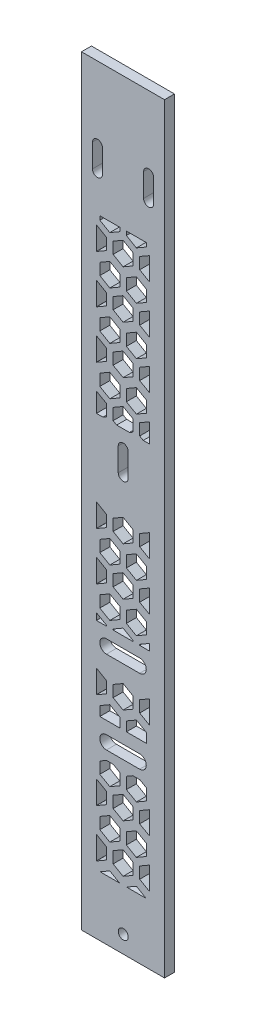
SolidWorks part; units mm, degrees
ref_plane "Front Plane" through (0, 0, 0) normal (0, 0, 1) x (1, 0, 0)
ref_plane "Top Plane" through (0, 0, 0) normal (0, 1, 0) x (1, 0, 0)
ref_plane "Right Plane" through (0, 0, 0) normal (1, 0, 0) x (0, 0, -1)
sketch "Sketch1" plane through (0, 0, 0) normal (0, 0, 1) x (1, 0, 0)
  line B0 (0, 114.5304) -> (25, 114.5304)
  line B1 (0, 114.5304) -> (0, -114.5304)
  line B2 (0, -114.5304) -> (25, -114.5304)
  line B3 (25, 114.5304) -> (25, -114.5304)
  line B4 (3.3, 89.1304) -> (0, 89.1304) construction
  line B5 (21.7, 89.1304) -> (25, 89.1304) construction
  line B6 (0, -100.1081) -> (25, -100.1081) construction
  circle B7 centre (4.8, 89.1304) radius 1.5
  circle B8 centre (20.2, 89.1304) radius 1.5
  circle B9 centre (12.5588, 13.7722) radius 1.5
  spline B10 degree 3 poles (11.075, -109.3281) (11.075, -112.3281) (14.075, -112.3281) (14.075, -109.3281) (14.075, -106.3281) (11.075, -106.3281) (11.075, -109.3281) (11.075, -112.3281) (14.075, -112.3281) knots -0.5 0 0 0 0.5 0.5 0.5 1 1 1 1.5 1.5 1.5 weights 1 0.333333 0.333333 1 0.333333 0.333333 1 0.333333 0.333333 only from (11.075, -109.3281) to (11.075, -109.3281)
sketch_block_instance "Block-sideExtraSupport-1"
sketch_block "Block-sideExtraSupport" parameters "D1"=25
extrude "Boss-Extrude1" add sketch "Sketch1" along normal blind 3 contours B1 B6 B3 B0 B9 B8 B7
sketch "Sketch2" plane through (0, 0, 3) normal (0, 0, 1) x (1, 0, 0)
  line L1 (0, -114.5304) -> (25, -114.5304) construction
  point P3 (12.5, -114.5304)
  line B0 (0, -24.3132) -> (40.525, -24.3132) construction
  line B1 (0, -24.3132) -> (0, -74.3132) construction
  line B2 (0, -74.3132) -> (40.525, -74.3132) construction
  line B3 (40.525, -24.3132) -> (40.525, -74.3132) construction
  line B4 (32.525, -24.3132) -> (28.125, -24.3132) construction
  line B5 (20.2625, -24.3132) -> (20.2625, -49.3132) construction
  line B6 (20.2625, -49.3132) -> (0, -49.3132) construction
  line B7 (20.2625, -36.8132) -> (0, -36.8132) construction
  line B8 (28.125, -64.3132) -> (32.525, -64.3132) construction
  line B9 (32.525, -64.3132) -> (32.525, -34.3132) construction
  line B10 (28.125, -64.3132) -> (28.125, -34.3132) construction
  line B11 (28.125, -34.3132) -> (32.525, -34.3132) construction
  line B12 (27.625, -64.8132) -> (33.025, -64.8132) construction
  line B13 (33.025, -64.8132) -> (33.025, -33.8132) construction
  line B14 (27.625, -33.8132) -> (33.025, -33.8132) construction
  line B15 (27.625, -64.8132) -> (27.625, -33.8132) construction
  line B16 (0, -100.1081) -> (25, -100.1081) construction
  line B17 (25, -114.5304) -> (0, -114.5304) construction
  line B18 (12.5, -100.1081) -> (12.5, -61.8132) construction
  line B19 (12.5, -114.5304) -> (12.5, -100.1081) construction
  line B20 (7.5, -36.8132) -> (17.5, -36.8132)
  line B21 (7.5, -34.8132) -> (17.5, -34.8132)
  line B22 (7.5, -38.8132) -> (17.5, -38.8132)
  line B23 (7.5, -61.8132) -> (17.5, -61.8132)
  line B24 (7.5, -63.8132) -> (17.5, -63.8132)
  line B25 (7.5, -59.8132) -> (17.5, -59.8132)
  arc B26 (7.5, -34.8132) -> (7.5, -38.8132) centre (7.5, -36.8132) ccw
  arc B27 (17.5, -38.8132) -> (17.5, -34.8132) centre (17.5, -36.8132) ccw
  arc B28 (7.5, -63.8132) -> (7.5, -59.8132) centre (7.5, -61.8132) cw
  arc B29 (17.5, -59.8132) -> (17.5, -63.8132) centre (17.5, -61.8132) cw
sketch_block_instance "Block-SidePanelSketch2-1"
sketch_block "Block-SidePanelSketch2" parameters "D1"=50, "D2"=4, "D3"=10, "D4"=8
extrude "Cut-Extrude1" cut sketch "Sketch2" against normal through all
sketch "Sketch3" plane through (0, 0, 3) normal (0, 0, 1) x (1, 0, 0)
  line L0 (12.5, 114.5304) -> (12.5, -114.5304) construction
  line L1 (0, 114.5304) -> (25, 114.5304) construction
  line L2 (0, -114.5304) -> (25, -114.5304) construction
  line L3 (4.8, 92.6304) -> (4.8, 85.6304) construction
  line L4 (6.3, 92.6304) -> (6.3, 85.6304)
  line L5 (3.3, 92.6304) -> (3.3, 85.6304)
  line L6 (20.2, 92.6304) -> (20.2, 85.6304) construction
  line L7 (18.7, 92.6304) -> (18.7, 85.6304)
  line L8 (21.7, 92.6304) -> (21.7, 85.6304)
  line L9 (12.5588, 17.2722) -> (12.5588, 10.2722) construction
  line L10 (14.0588, 17.2722) -> (14.0588, 10.2722)
  line L11 (11.0588, 17.2722) -> (11.0588, 10.2722)
  arc A1 (6.3, 92.6304) -> (3.3, 92.6304) centre (4.8, 92.6304) ccw
  arc A2 (3.3, 85.6304) -> (6.3, 85.6304) centre (4.8, 85.6304) ccw
  circle A3 centre (4.8, 89.1304) radius 1.5 construction
  arc A4 (18.7, 92.6304) -> (21.7, 92.6304) centre (20.2, 92.6304) cw
  arc A5 (21.7, 85.6304) -> (18.7, 85.6304) centre (20.2, 85.6304) cw
  arc A6 (14.0588, 17.2722) -> (11.0588, 17.2722) centre (12.5588, 17.2722) ccw
  arc A7 (11.0588, 10.2722) -> (14.0588, 10.2722) centre (12.5588, 10.2722) ccw
  circle A8 centre (12.5588, 13.7722) radius 1.5 construction
  point P6 (4.8, 89.1304)
  point P10 (12.5588, 18.7722)
  point P14 (12.5588, 13.7722)
  point P19 (4.8, 94.1304)
  point P22 (20.2, 89.1304)
  dimension "D1" = 5
  dimension "D2" = 5
extrude "Cut-Extrude2" cut sketch "Sketch3" against normal through all
sketch "Sketch4" plane through (0, 0, 3) normal (0, 0, 1) x (1, 0, 0)
  line L0 (25, 114.5304) -> (25, -114.5304) construction
  line L1 (4.5, -66.5304) -> (20.5, -66.5304)
  line L2 (4.5, -66.5304) -> (4.5, -96.5304)
  line L3 (4.5, -96.5304) -> (20.5, -96.5304)
  line L4 (20.5, -66.5304) -> (20.5, -96.5304)
  line L5 (4.5, -66.5304) -> (20.5, -96.5304) construction
  line L6 (4.5, -96.5304) -> (20.5, -66.5304) construction
  line L7 (4.5, -43.0716) -> (20.5, -43.0716)
  line L8 (4.5, -43.0716) -> (4.5, -56.0716)
  line L9 (4.5, -56.0716) -> (20.5, -56.0716)
  line L10 (20.5, -43.0716) -> (20.5, -56.0716)
  line L11 (4.5, -43.0716) -> (20.5, -56.0716) construction
  line L12 (4.5, -56.0716) -> (20.5, -43.0716) construction
  line L13 (4.5, 22.4696) -> (20.5, 22.4696)
  line L14 (4.5, 22.4696) -> (4.5, 74.5304)
  line L15 (4.5, 74.5304) -> (20.5, 74.5304)
  line L16 (20.5, 22.4696) -> (20.5, 74.5304)
  line L17 (4.5, 22.4696) -> (20.5, 74.5304) construction
  line L18 (4.5, 74.5304) -> (20.5, 22.4696) construction
  line L19 (4.5, -31.5304) -> (20.5, -31.5304)
  line L20 (4.5, -31.5304) -> (4.5, 5.4696)
  line L21 (4.5, 5.4696) -> (20.5, 5.4696)
  line L22 (20.5, -31.5304) -> (20.5, 5.4696)
  line L23 (4.5, -31.5304) -> (20.5, 5.4696) construction
  line L24 (4.5, 5.4696) -> (20.5, -31.5304) construction
  line L25 (0, 114.5304) -> (0, -114.5304) construction
  line L26 (0, -114.5304) -> (25, -114.5304) construction
  line L27 (0, 114.5304) -> (25, 114.5304) construction
  line L28 (11.5204, -100.036) -> (11.5204, -96.5719)
  line L29 (3.5204, -100.036) -> (3.5204, -96.5719)
  line L30 (3.5204, -96.5719) -> (0.5204, -94.8398)
  line L31 (0.5204, -94.8398) -> (-2.4796, -96.5719)
  line L32 (-2.4796, -96.5719) -> (-2.4796, -100.036)
  line L33 (-2.4796, -100.036) -> (0.5204, -101.7681)
  line L34 (0.5204, -101.7681) -> (3.5204, -100.036)
  line L35 (7.5204, -106.9642) -> (7.5204, -103.5001)
  line L36 (7.5204, -103.5001) -> (4.5204, -101.7681)
  line L37 (4.5204, -101.7681) -> (1.5204, -103.5001)
  line L38 (1.5204, -103.5001) -> (1.5204, -106.9642)
  line L39 (1.5204, -106.9642) -> (4.5204, -108.6963)
  line L40 (4.5204, -108.6963) -> (7.5204, -106.9642)
  line L41 (11.5204, -96.5719) -> (8.5204, -94.8398)
  line L42 (8.5204, -94.8398) -> (5.5204, -96.5719)
  line L43 (5.5204, -96.5719) -> (5.5204, -100.036)
  line L44 (5.5204, -100.036) -> (8.5204, -101.7681)
  line L45 (8.5204, -101.7681) -> (11.5204, -100.036)
  line L46 (15.5204, -106.9642) -> (15.5204, -103.5001)
  line L47 (15.5204, -103.5001) -> (12.5204, -101.7681)
  line L48 (12.5204, -101.7681) -> (9.5204, -103.5001)
  line L49 (9.5204, -103.5001) -> (9.5204, -106.9642)
  line L50 (9.5204, -106.9642) -> (12.5204, -108.6963)
  line L51 (12.5204, -108.6963) -> (15.5204, -106.9642)
  line L52 (19.5204, -100.036) -> (19.5204, -96.5719)
  line L53 (19.5204, -96.5719) -> (16.5204, -94.8398)
  line L54 (16.5204, -94.8398) -> (13.5204, -96.5719)
  line L55 (13.5204, -96.5719) -> (13.5204, -100.036)
  line L56 (13.5204, -100.036) -> (16.5204, -101.7681)
  line L57 (16.5204, -101.7681) -> (19.5204, -100.036)
  line L58 (23.5204, -106.9642) -> (23.5204, -103.5001)
  line L59 (23.5204, -103.5001) -> (20.5204, -101.7681)
  line L60 (20.5204, -101.7681) -> (17.5204, -103.5001)
  line L61 (17.5204, -103.5001) -> (17.5204, -106.9642)
  line L62 (17.5204, -106.9642) -> (20.5204, -108.6963)
  line L63 (20.5204, -108.6963) -> (23.5204, -106.9642)
  line L64 (11.5204, -85.586) -> (11.5204, -82.1219)
  line L65 (11.5204, -82.1219) -> (8.5204, -80.3898)
  line L66 (8.5204, -80.3898) -> (5.5204, -82.1219)
  line L67 (5.5204, -82.1219) -> (5.5204, -85.586)
  line L68 (5.5204, -85.586) -> (8.5204, -87.3181)
  line L69 (8.5204, -87.3181) -> (11.5204, -85.586)
  line L70 (15.5204, -92.5142) -> (15.5204, -89.0501)
  line L71 (15.5204, -89.0501) -> (12.5204, -87.3181)
  line L72 (12.5204, -87.3181) -> (9.5204, -89.0501)
  line L73 (9.5204, -89.0501) -> (9.5204, -92.5142)
  line L74 (9.5204, -92.5142) -> (12.5204, -94.2463)
  line L75 (12.5204, -94.2463) -> (15.5204, -92.5142)
  line L76 (19.5204, -85.586) -> (19.5204, -82.1219)
  line L77 (19.5204, -82.1219) -> (16.5204, -80.3898)
  line L78 (16.5204, -80.3898) -> (13.5204, -82.1219)
  line L79 (13.5204, -82.1219) -> (13.5204, -85.586)
  line L80 (13.5204, -85.586) -> (16.5204, -87.3181)
  line L81 (16.5204, -87.3181) -> (19.5204, -85.586)
  line L82 (23.5204, -92.5142) -> (23.5204, -89.0501)
  line L83 (23.5204, -89.0501) -> (20.5204, -87.3181)
  line L84 (20.5204, -87.3181) -> (17.5204, -89.0501)
  line L85 (17.5204, -89.0501) -> (17.5204, -92.5142)
  line L86 (17.5204, -92.5142) -> (20.5204, -94.2463)
  line L87 (20.5204, -94.2463) -> (23.5204, -92.5142)
  line L88 (11.5204, -71.136) -> (11.5204, -67.6719)
  line L89 (11.5204, -67.6719) -> (8.5204, -65.9398)
  line L90 (8.5204, -65.9398) -> (5.5204, -67.6719)
  line L91 (5.5204, -67.6719) -> (5.5204, -71.136)
  line L92 (5.5204, -71.136) -> (8.5204, -72.8681)
  line L93 (8.5204, -72.8681) -> (11.5204, -71.136)
  line L94 (15.5204, -78.0642) -> (15.5204, -74.6001)
  line L95 (15.5204, -74.6001) -> (12.5204, -72.8681)
  line L96 (12.5204, -72.8681) -> (9.5204, -74.6001)
  line L97 (9.5204, -74.6001) -> (9.5204, -78.0642)
  line L98 (9.5204, -78.0642) -> (12.5204, -79.7963)
  line L99 (12.5204, -79.7963) -> (15.5204, -78.0642)
  line L100 (19.5204, -71.136) -> (19.5204, -67.6719)
  line L101 (19.5204, -67.6719) -> (16.5204, -65.9398)
  line L102 (16.5204, -65.9398) -> (13.5204, -67.6719)
  line L103 (13.5204, -67.6719) -> (13.5204, -71.136)
  line L104 (13.5204, -71.136) -> (16.5204, -72.8681)
  line L105 (16.5204, -72.8681) -> (19.5204, -71.136)
  line L106 (23.5204, -78.0642) -> (23.5204, -74.6001)
  line L107 (23.5204, -74.6001) -> (20.5204, -72.8681)
  line L108 (20.5204, -72.8681) -> (17.5204, -74.6001)
  line L109 (17.5204, -74.6001) -> (17.5204, -78.0642)
  line L110 (17.5204, -78.0642) -> (20.5204, -79.7963)
  line L111 (20.5204, -79.7963) -> (23.5204, -78.0642)
  line L112 (11.5204, -56.686) -> (11.5204, -53.2219)
  line L113 (11.5204, -53.2219) -> (8.5204, -51.4898)
  line L114 (8.5204, -51.4898) -> (5.5204, -53.2219)
  line L115 (5.5204, -53.2219) -> (5.5204, -56.686)
  line L116 (5.5204, -56.686) -> (8.5204, -58.4181)
  line L117 (8.5204, -58.4181) -> (11.5204, -56.686)
  line L118 (15.5204, -63.6142) -> (15.5204, -60.1501)
  line L119 (15.5204, -60.1501) -> (12.5204, -58.4181)
  line L120 (12.5204, -58.4181) -> (9.5204, -60.1501)
  line L121 (9.5204, -60.1501) -> (9.5204, -63.6142)
  line L122 (9.5204, -63.6142) -> (12.5204, -65.3463)
  line L123 (12.5204, -65.3463) -> (15.5204, -63.6142)
  line L124 (19.5204, -56.686) -> (19.5204, -53.2219)
  line L125 (19.5204, -53.2219) -> (16.5204, -51.4898)
  line L126 (16.5204, -51.4898) -> (13.5204, -53.2219)
  line L127 (13.5204, -53.2219) -> (13.5204, -56.686)
  line L128 (13.5204, -56.686) -> (16.5204, -58.4181)
  line L129 (16.5204, -58.4181) -> (19.5204, -56.686)
  line L130 (23.5204, -63.6142) -> (23.5204, -60.1501)
  line L131 (23.5204, -60.1501) -> (20.5204, -58.4181)
  line L132 (20.5204, -58.4181) -> (17.5204, -60.1501)
  line L133 (17.5204, -60.1501) -> (17.5204, -63.6142)
  line L134 (17.5204, -63.6142) -> (20.5204, -65.3463)
  line L135 (20.5204, -65.3463) -> (23.5204, -63.6142)
  line L136 (11.5204, -42.236) -> (11.5204, -38.7719)
  line L137 (11.5204, -38.7719) -> (8.5204, -37.0398)
  line L138 (8.5204, -37.0398) -> (5.5204, -38.7719)
  line L139 (5.5204, -38.7719) -> (5.5204, -42.236)
  line L140 (5.5204, -42.236) -> (8.5204, -43.9681)
  line L141 (8.5204, -43.9681) -> (11.5204, -42.236)
  line L142 (15.5204, -49.1642) -> (15.5204, -45.7001)
  line L143 (15.5204, -45.7001) -> (12.5204, -43.9681)
  line L144 (12.5204, -43.9681) -> (9.5204, -45.7001)
  line L145 (9.5204, -45.7001) -> (9.5204, -49.1642)
  line L146 (9.5204, -49.1642) -> (12.5204, -50.8963)
  line L147 (12.5204, -50.8963) -> (15.5204, -49.1642)
  line L148 (19.5204, -42.236) -> (19.5204, -38.7719)
  line L149 (19.5204, -38.7719) -> (16.5204, -37.0398)
  line L150 (16.5204, -37.0398) -> (13.5204, -38.7719)
  line L151 (13.5204, -38.7719) -> (13.5204, -42.236)
  line L152 (13.5204, -42.236) -> (16.5204, -43.9681)
  line L153 (16.5204, -43.9681) -> (19.5204, -42.236)
  line L154 (23.5204, -49.1642) -> (23.5204, -45.7001)
  line L155 (23.5204, -45.7001) -> (20.5204, -43.9681)
  line L156 (20.5204, -43.9681) -> (17.5204, -45.7001)
  line L157 (17.5204, -45.7001) -> (17.5204, -49.1642)
  line L158 (17.5204, -49.1642) -> (20.5204, -50.8963)
  line L159 (20.5204, -50.8963) -> (23.5204, -49.1642)
  line L160 (11.5204, -27.786) -> (11.5204, -24.3219)
  line L161 (11.5204, -24.3219) -> (8.5204, -22.5898)
  line L162 (8.5204, -22.5898) -> (5.5204, -24.3219)
  line L163 (5.5204, -24.3219) -> (5.5204, -27.786)
  line L164 (5.5204, -27.786) -> (8.5204, -29.5181)
  line L165 (8.5204, -29.5181) -> (11.5204, -27.786)
  line L166 (15.5204, -34.7142) -> (15.5204, -31.2501)
  line L167 (15.5204, -31.2501) -> (12.5204, -29.5181)
  line L168 (12.5204, -29.5181) -> (9.5204, -31.2501)
  line L169 (9.5204, -31.2501) -> (9.5204, -34.7142)
  line L170 (9.5204, -34.7142) -> (12.5204, -36.4463)
  line L171 (12.5204, -36.4463) -> (15.5204, -34.7142)
  line L172 (19.5204, -27.786) -> (19.5204, -24.3219)
  line L173 (19.5204, -24.3219) -> (16.5204, -22.5898)
  line L174 (16.5204, -22.5898) -> (13.5204, -24.3219)
  line L175 (13.5204, -24.3219) -> (13.5204, -27.786)
  line L176 (13.5204, -27.786) -> (16.5204, -29.5181)
  line L177 (16.5204, -29.5181) -> (19.5204, -27.786)
  line L178 (23.5204, -34.7142) -> (23.5204, -31.2501)
  line L179 (23.5204, -31.2501) -> (20.5204, -29.5181)
  line L180 (20.5204, -29.5181) -> (17.5204, -31.2501)
  line L181 (17.5204, -31.2501) -> (17.5204, -34.7142)
  line L182 (17.5204, -34.7142) -> (20.5204, -36.4463)
  line L183 (20.5204, -36.4463) -> (23.5204, -34.7142)
  line L184 (11.5204, -13.336) -> (11.5204, -9.8719)
  line L185 (11.5204, -9.8719) -> (8.5204, -8.1398)
  line L186 (8.5204, -8.1398) -> (5.5204, -9.8719)
  line L187 (5.5204, -9.8719) -> (5.5204, -13.336)
  line L188 (5.5204, -13.336) -> (8.5204, -15.0681)
  line L189 (8.5204, -15.0681) -> (11.5204, -13.336)
  line L190 (15.5204, -20.2642) -> (15.5204, -16.8001)
  line L191 (15.5204, -16.8001) -> (12.5204, -15.0681)
  line L192 (12.5204, -15.0681) -> (9.5204, -16.8001)
  line L193 (9.5204, -16.8001) -> (9.5204, -20.2642)
  line L194 (9.5204, -20.2642) -> (12.5204, -21.9963)
  line L195 (12.5204, -21.9963) -> (15.5204, -20.2642)
  line L196 (19.5204, -13.336) -> (19.5204, -9.8719)
  line L197 (19.5204, -9.8719) -> (16.5204, -8.1398)
  line L198 (16.5204, -8.1398) -> (13.5204, -9.8719)
  line L199 (13.5204, -9.8719) -> (13.5204, -13.336)
  line L200 (13.5204, -13.336) -> (16.5204, -15.0681)
  line L201 (16.5204, -15.0681) -> (19.5204, -13.336)
  line L202 (23.5204, -20.2642) -> (23.5204, -16.8001)
  line L203 (23.5204, -16.8001) -> (20.5204, -15.0681)
  line L204 (20.5204, -15.0681) -> (17.5204, -16.8001)
  line L205 (17.5204, -16.8001) -> (17.5204, -20.2642)
  line L206 (17.5204, -20.2642) -> (20.5204, -21.9963)
  line L207 (20.5204, -21.9963) -> (23.5204, -20.2642)
  line L208 (11.5204, 1.114) -> (11.5204, 4.5781)
  line L209 (11.5204, 4.5781) -> (8.5204, 6.3102)
  line L210 (8.5204, 6.3102) -> (5.5204, 4.5781)
  line L211 (5.5204, 4.5781) -> (5.5204, 1.114)
  line L212 (5.5204, 1.114) -> (8.5204, -0.6181)
  line L213 (8.5204, -0.6181) -> (11.5204, 1.114)
  line L214 (15.5204, -5.8142) -> (15.5204, -2.3501)
  line L215 (15.5204, -2.3501) -> (12.5204, -0.6181)
  line L216 (12.5204, -0.6181) -> (9.5204, -2.3501)
  line L217 (9.5204, -2.3501) -> (9.5204, -5.8142)
  line L218 (9.5204, -5.8142) -> (12.5204, -7.5463)
  line L219 (12.5204, -7.5463) -> (15.5204, -5.8142)
  line L220 (19.5204, 1.114) -> (19.5204, 4.5781)
  line L221 (19.5204, 4.5781) -> (16.5204, 6.3102)
  line L222 (16.5204, 6.3102) -> (13.5204, 4.5781)
  line L223 (13.5204, 4.5781) -> (13.5204, 1.114)
  line L224 (13.5204, 1.114) -> (16.5204, -0.6181)
  line L225 (16.5204, -0.6181) -> (19.5204, 1.114)
  line L226 (23.5204, -5.8142) -> (23.5204, -2.3501)
  line L227 (23.5204, -2.3501) -> (20.5204, -0.6181)
  line L228 (20.5204, -0.6181) -> (17.5204, -2.3501)
  line L229 (17.5204, -2.3501) -> (17.5204, -5.8142)
  line L230 (17.5204, -5.8142) -> (20.5204, -7.5463)
  line L231 (20.5204, -7.5463) -> (23.5204, -5.8142)
  line L232 (11.5204, 15.564) -> (11.5204, 19.0281)
  line L233 (11.5204, 19.0281) -> (8.5204, 20.7602)
  line L234 (8.5204, 20.7602) -> (5.5204, 19.0281)
  line L235 (5.5204, 19.0281) -> (5.5204, 15.564)
  line L236 (5.5204, 15.564) -> (8.5204, 13.8319)
  line L237 (8.5204, 13.8319) -> (11.5204, 15.564)
  line L238 (15.5204, 8.6358) -> (15.5204, 12.0999)
  line L239 (15.5204, 12.0999) -> (12.5204, 13.8319)
  line L240 (12.5204, 13.8319) -> (9.5204, 12.0999)
  line L241 (9.5204, 12.0999) -> (9.5204, 8.6358)
  line L242 (9.5204, 8.6358) -> (12.5204, 6.9037)
  line L243 (12.5204, 6.9037) -> (15.5204, 8.6358)
  line L244 (19.5204, 15.564) -> (19.5204, 19.0281)
  line L245 (19.5204, 19.0281) -> (16.5204, 20.7602)
  line L246 (16.5204, 20.7602) -> (13.5204, 19.0281)
  line L247 (13.5204, 19.0281) -> (13.5204, 15.564)
  line L248 (13.5204, 15.564) -> (16.5204, 13.8319)
  line L249 (16.5204, 13.8319) -> (19.5204, 15.564)
  line L250 (23.5204, 8.6358) -> (23.5204, 12.0999)
  line L251 (23.5204, 12.0999) -> (20.5204, 13.8319)
  line L252 (20.5204, 13.8319) -> (17.5204, 12.0999)
  line L253 (17.5204, 12.0999) -> (17.5204, 8.6358)
  line L254 (17.5204, 8.6358) -> (20.5204, 6.9037)
  line L255 (20.5204, 6.9037) -> (23.5204, 8.6358)
  line L256 (11.5204, 30.014) -> (11.5204, 33.4781)
  line L257 (11.5204, 33.4781) -> (8.5204, 35.2102)
  line L258 (8.5204, 35.2102) -> (5.5204, 33.4781)
  line L259 (5.5204, 33.4781) -> (5.5204, 30.014)
  line L260 (5.5204, 30.014) -> (8.5204, 28.2819)
  line L261 (8.5204, 28.2819) -> (11.5204, 30.014)
  line L262 (15.5204, 23.0858) -> (15.5204, 26.5499)
  line L263 (15.5204, 26.5499) -> (12.5204, 28.2819)
  line L264 (12.5204, 28.2819) -> (9.5204, 26.5499)
  line L265 (9.5204, 26.5499) -> (9.5204, 23.0858)
  line L266 (9.5204, 23.0858) -> (12.5204, 21.3537)
  line L267 (12.5204, 21.3537) -> (15.5204, 23.0858)
  line L268 (19.5204, 30.014) -> (19.5204, 33.4781)
  line L269 (19.5204, 33.4781) -> (16.5204, 35.2102)
  line L270 (16.5204, 35.2102) -> (13.5204, 33.4781)
  line L271 (13.5204, 33.4781) -> (13.5204, 30.014)
  line L272 (13.5204, 30.014) -> (16.5204, 28.2819)
  line L273 (16.5204, 28.2819) -> (19.5204, 30.014)
  line L274 (23.5204, 23.0858) -> (23.5204, 26.5499)
  line L275 (23.5204, 26.5499) -> (20.5204, 28.2819)
  line L276 (20.5204, 28.2819) -> (17.5204, 26.5499)
  line L277 (17.5204, 26.5499) -> (17.5204, 23.0858)
  line L278 (17.5204, 23.0858) -> (20.5204, 21.3537)
  line L279 (20.5204, 21.3537) -> (23.5204, 23.0858)
  line L280 (11.5204, 44.464) -> (11.5204, 47.9281)
  line L281 (11.5204, 47.9281) -> (8.5204, 49.6602)
  line L282 (8.5204, 49.6602) -> (5.5204, 47.9281)
  line L283 (5.5204, 47.9281) -> (5.5204, 44.464)
  line L284 (5.5204, 44.464) -> (8.5204, 42.7319)
  line L285 (8.5204, 42.7319) -> (11.5204, 44.464)
  line L286 (15.5204, 37.5358) -> (15.5204, 40.9999)
  line L287 (15.5204, 40.9999) -> (12.5204, 42.7319)
  line L288 (12.5204, 42.7319) -> (9.5204, 40.9999)
  line L289 (9.5204, 40.9999) -> (9.5204, 37.5358)
  line L290 (9.5204, 37.5358) -> (12.5204, 35.8037)
  line L291 (12.5204, 35.8037) -> (15.5204, 37.5358)
  line L292 (19.5204, 44.464) -> (19.5204, 47.9281)
  line L293 (19.5204, 47.9281) -> (16.5204, 49.6602)
  line L294 (16.5204, 49.6602) -> (13.5204, 47.9281)
  line L295 (13.5204, 47.9281) -> (13.5204, 44.464)
  line L296 (13.5204, 44.464) -> (16.5204, 42.7319)
  line L297 (16.5204, 42.7319) -> (19.5204, 44.464)
  line L298 (23.5204, 37.5358) -> (23.5204, 40.9999)
  line L299 (23.5204, 40.9999) -> (20.5204, 42.7319)
  line L300 (20.5204, 42.7319) -> (17.5204, 40.9999)
  line L301 (17.5204, 40.9999) -> (17.5204, 37.5358)
  line L302 (17.5204, 37.5358) -> (20.5204, 35.8037)
  line L303 (20.5204, 35.8037) -> (23.5204, 37.5358)
  line L304 (11.5204, 58.914) -> (11.5204, 62.3781)
  line L305 (11.5204, 62.3781) -> (8.5204, 64.1102)
  line L306 (8.5204, 64.1102) -> (5.5204, 62.3781)
  line L307 (5.5204, 62.3781) -> (5.5204, 58.914)
  line L308 (5.5204, 58.914) -> (8.5204, 57.1819)
  line L309 (8.5204, 57.1819) -> (11.5204, 58.914)
  line L310 (15.5204, 51.9858) -> (15.5204, 55.4499)
  line L311 (15.5204, 55.4499) -> (12.5204, 57.1819)
  line L312 (12.5204, 57.1819) -> (9.5204, 55.4499)
  line L313 (9.5204, 55.4499) -> (9.5204, 51.9858)
  line L314 (9.5204, 51.9858) -> (12.5204, 50.2537)
  line L315 (12.5204, 50.2537) -> (15.5204, 51.9858)
  line L316 (19.5204, 58.914) -> (19.5204, 62.3781)
  line L317 (19.5204, 62.3781) -> (16.5204, 64.1102)
  line L318 (16.5204, 64.1102) -> (13.5204, 62.3781)
  line L319 (13.5204, 62.3781) -> (13.5204, 58.914)
  line L320 (13.5204, 58.914) -> (16.5204, 57.1819)
  line L321 (16.5204, 57.1819) -> (19.5204, 58.914)
  line L322 (23.5204, 51.9858) -> (23.5204, 55.4499)
  line L323 (23.5204, 55.4499) -> (20.5204, 57.1819)
  line L324 (20.5204, 57.1819) -> (17.5204, 55.4499)
  line L325 (17.5204, 55.4499) -> (17.5204, 51.9858)
  line L326 (17.5204, 51.9858) -> (20.5204, 50.2537)
  line L327 (20.5204, 50.2537) -> (23.5204, 51.9858)
  line L328 (11.5204, 73.364) -> (11.5204, 76.8281)
  line L329 (11.5204, 76.8281) -> (8.5204, 78.5602)
  line L330 (8.5204, 78.5602) -> (5.5204, 76.8281)
  line L331 (5.5204, 76.8281) -> (5.5204, 73.364)
  line L332 (5.5204, 73.364) -> (8.5204, 71.6319)
  line L333 (8.5204, 71.6319) -> (11.5204, 73.364)
  line L334 (15.5204, 66.4358) -> (15.5204, 69.8999)
  line L335 (15.5204, 69.8999) -> (12.5204, 71.6319)
  line L336 (12.5204, 71.6319) -> (9.5204, 69.8999)
  line L337 (9.5204, 69.8999) -> (9.5204, 66.4358)
  line L338 (9.5204, 66.4358) -> (12.5204, 64.7037)
  line L339 (12.5204, 64.7037) -> (15.5204, 66.4358)
  line L340 (19.5204, 73.364) -> (19.5204, 76.8281)
  line L341 (19.5204, 76.8281) -> (16.5204, 78.5602)
  line L342 (16.5204, 78.5602) -> (13.5204, 76.8281)
  line L343 (13.5204, 76.8281) -> (13.5204, 73.364)
  line L344 (13.5204, 73.364) -> (16.5204, 71.6319)
  line L345 (16.5204, 71.6319) -> (19.5204, 73.364)
  line L346 (23.5204, 66.4358) -> (23.5204, 69.8999)
  line L347 (23.5204, 69.8999) -> (20.5204, 71.6319)
  line L348 (20.5204, 71.6319) -> (17.5204, 69.8999)
  line L349 (17.5204, 69.8999) -> (17.5204, 66.4358)
  line L350 (17.5204, 66.4358) -> (20.5204, 64.7037)
  line L351 (20.5204, 64.7037) -> (23.5204, 66.4358)
  line L352 (3.5204, -85.586) -> (3.5204, -82.1219)
  line L353 (3.5204, -82.1219) -> (0.5204, -80.3898)
  line L354 (0.5204, -80.3898) -> (-2.4796, -82.1219)
  line L355 (-2.4796, -82.1219) -> (-2.4796, -85.586)
  line L356 (-2.4796, -85.586) -> (0.5204, -87.3181)
  line L357 (0.5204, -87.3181) -> (3.5204, -85.586)
  line L358 (7.5204, -92.5142) -> (7.5204, -89.0501)
  line L359 (7.5204, -89.0501) -> (4.5204, -87.3181)
  line L360 (4.5204, -87.3181) -> (1.5204, -89.0501)
  line L361 (1.5204, -89.0501) -> (1.5204, -92.5142)
  line L362 (1.5204, -92.5142) -> (4.5204, -94.2463)
  line L363 (4.5204, -94.2463) -> (7.5204, -92.5142)
  line L364 (3.5204, -71.136) -> (3.5204, -67.6719)
  line L365 (3.5204, -67.6719) -> (0.5204, -65.9398)
  line L366 (0.5204, -65.9398) -> (-2.4796, -67.6719)
  line L367 (-2.4796, -67.6719) -> (-2.4796, -71.136)
  line L368 (-2.4796, -71.136) -> (0.5204, -72.8681)
  line L369 (0.5204, -72.8681) -> (3.5204, -71.136)
  line L370 (7.5204, -78.0642) -> (7.5204, -74.6001)
  line L371 (7.5204, -74.6001) -> (4.5204, -72.8681)
  line L372 (4.5204, -72.8681) -> (1.5204, -74.6001)
  line L373 (1.5204, -74.6001) -> (1.5204, -78.0642)
  line L374 (1.5204, -78.0642) -> (4.5204, -79.7963)
  line L375 (4.5204, -79.7963) -> (7.5204, -78.0642)
  line L376 (3.5204, -56.686) -> (3.5204, -53.2219)
  line L377 (3.5204, -53.2219) -> (0.5204, -51.4898)
  line L378 (0.5204, -51.4898) -> (-2.4796, -53.2219)
  line L379 (-2.4796, -53.2219) -> (-2.4796, -56.686)
  line L380 (-2.4796, -56.686) -> (0.5204, -58.4181)
  line L381 (0.5204, -58.4181) -> (3.5204, -56.686)
  line L382 (7.5204, -63.6142) -> (7.5204, -60.1501)
  line L383 (7.5204, -60.1501) -> (4.5204, -58.4181)
  line L384 (4.5204, -58.4181) -> (1.5204, -60.1501)
  line L385 (1.5204, -60.1501) -> (1.5204, -63.6142)
  line L386 (1.5204, -63.6142) -> (4.5204, -65.3463)
  line L387 (4.5204, -65.3463) -> (7.5204, -63.6142)
  line L388 (3.5204, -42.236) -> (3.5204, -38.7719)
  line L389 (3.5204, -38.7719) -> (0.5204, -37.0398)
  line L390 (0.5204, -37.0398) -> (-2.4796, -38.7719)
  line L391 (-2.4796, -38.7719) -> (-2.4796, -42.236)
  line L392 (-2.4796, -42.236) -> (0.5204, -43.9681)
  line L393 (0.5204, -43.9681) -> (3.5204, -42.236)
  line L394 (7.5204, -49.1642) -> (7.5204, -45.7001)
  line L395 (7.5204, -45.7001) -> (4.5204, -43.9681)
  line L396 (4.5204, -43.9681) -> (1.5204, -45.7001)
  line L397 (1.5204, -45.7001) -> (1.5204, -49.1642)
  line L398 (1.5204, -49.1642) -> (4.5204, -50.8963)
  line L399 (4.5204, -50.8963) -> (7.5204, -49.1642)
  line L400 (3.5204, -27.786) -> (3.5204, -24.3219)
  line L401 (3.5204, -24.3219) -> (0.5204, -22.5898)
  line L402 (0.5204, -22.5898) -> (-2.4796, -24.3219)
  line L403 (-2.4796, -24.3219) -> (-2.4796, -27.786)
  line L404 (-2.4796, -27.786) -> (0.5204, -29.5181)
  line L405 (0.5204, -29.5181) -> (3.5204, -27.786)
  line L406 (7.5204, -34.7142) -> (7.5204, -31.2501)
  line L407 (7.5204, -31.2501) -> (4.5204, -29.5181)
  line L408 (4.5204, -29.5181) -> (1.5204, -31.2501)
  line L409 (1.5204, -31.2501) -> (1.5204, -34.7142)
  line L410 (1.5204, -34.7142) -> (4.5204, -36.4463)
  line L411 (4.5204, -36.4463) -> (7.5204, -34.7142)
  line L412 (3.5204, -13.336) -> (3.5204, -9.8719)
  line L413 (3.5204, -9.8719) -> (0.5204, -8.1398)
  line L414 (0.5204, -8.1398) -> (-2.4796, -9.8719)
  line L415 (-2.4796, -9.8719) -> (-2.4796, -13.336)
  line L416 (-2.4796, -13.336) -> (0.5204, -15.0681)
  line L417 (0.5204, -15.0681) -> (3.5204, -13.336)
  line L418 (7.5204, -20.2642) -> (7.5204, -16.8001)
  line L419 (7.5204, -16.8001) -> (4.5204, -15.0681)
  line L420 (4.5204, -15.0681) -> (1.5204, -16.8001)
  line L421 (1.5204, -16.8001) -> (1.5204, -20.2642)
  line L422 (1.5204, -20.2642) -> (4.5204, -21.9963)
  line L423 (4.5204, -21.9963) -> (7.5204, -20.2642)
  line L424 (3.5204, 1.114) -> (3.5204, 4.5781)
  line L425 (3.5204, 4.5781) -> (0.5204, 6.3102)
  line L426 (0.5204, 6.3102) -> (-2.4796, 4.5781)
  line L427 (-2.4796, 4.5781) -> (-2.4796, 1.114)
  line L428 (-2.4796, 1.114) -> (0.5204, -0.6181)
  line L429 (0.5204, -0.6181) -> (3.5204, 1.114)
  line L430 (7.5204, -5.8142) -> (7.5204, -2.3501)
  line L431 (7.5204, -2.3501) -> (4.5204, -0.6181)
  line L432 (4.5204, -0.6181) -> (1.5204, -2.3501)
  line L433 (1.5204, -2.3501) -> (1.5204, -5.8142)
  line L434 (1.5204, -5.8142) -> (4.5204, -7.5463)
  line L435 (4.5204, -7.5463) -> (7.5204, -5.8142)
  line L436 (3.5204, 15.564) -> (3.5204, 19.0281)
  line L437 (3.5204, 19.0281) -> (0.5204, 20.7602)
  line L438 (0.5204, 20.7602) -> (-2.4796, 19.0281)
  line L439 (-2.4796, 19.0281) -> (-2.4796, 15.564)
  line L440 (-2.4796, 15.564) -> (0.5204, 13.8319)
  line L441 (0.5204, 13.8319) -> (3.5204, 15.564)
  line L442 (7.5204, 8.6358) -> (7.5204, 12.0999)
  line L443 (7.5204, 12.0999) -> (4.5204, 13.8319)
  line L444 (4.5204, 13.8319) -> (1.5204, 12.0999)
  line L445 (1.5204, 12.0999) -> (1.5204, 8.6358)
  line L446 (1.5204, 8.6358) -> (4.5204, 6.9037)
  line L447 (4.5204, 6.9037) -> (7.5204, 8.6358)
  line L448 (3.5204, 30.014) -> (3.5204, 33.4781)
  line L449 (3.5204, 33.4781) -> (0.5204, 35.2102)
  line L450 (0.5204, 35.2102) -> (-2.4796, 33.4781)
  line L451 (-2.4796, 33.4781) -> (-2.4796, 30.014)
  line L452 (-2.4796, 30.014) -> (0.5204, 28.2819)
  line L453 (0.5204, 28.2819) -> (3.5204, 30.014)
  line L454 (7.5204, 23.0858) -> (7.5204, 26.5499)
  line L455 (7.5204, 26.5499) -> (4.5204, 28.2819)
  line L456 (4.5204, 28.2819) -> (1.5204, 26.5499)
  line L457 (1.5204, 26.5499) -> (1.5204, 23.0858)
  line L458 (1.5204, 23.0858) -> (4.5204, 21.3537)
  line L459 (4.5204, 21.3537) -> (7.5204, 23.0858)
  line L460 (3.5204, 44.464) -> (3.5204, 47.9281)
  line L461 (3.5204, 47.9281) -> (0.5204, 49.6602)
  line L462 (0.5204, 49.6602) -> (-2.4796, 47.9281)
  line L463 (-2.4796, 47.9281) -> (-2.4796, 44.464)
  line L464 (-2.4796, 44.464) -> (0.5204, 42.7319)
  line L465 (0.5204, 42.7319) -> (3.5204, 44.464)
  line L466 (7.5204, 37.5358) -> (7.5204, 40.9999)
  line L467 (7.5204, 40.9999) -> (4.5204, 42.7319)
  line L468 (4.5204, 42.7319) -> (1.5204, 40.9999)
  line L469 (1.5204, 40.9999) -> (1.5204, 37.5358)
  line L470 (1.5204, 37.5358) -> (4.5204, 35.8037)
  line L471 (4.5204, 35.8037) -> (7.5204, 37.5358)
  line L472 (3.5204, 58.914) -> (3.5204, 62.3781)
  line L473 (3.5204, 62.3781) -> (0.5204, 64.1102)
  line L474 (0.5204, 64.1102) -> (-2.4796, 62.3781)
  line L475 (-2.4796, 62.3781) -> (-2.4796, 58.914)
  line L476 (-2.4796, 58.914) -> (0.5204, 57.1819)
  line L477 (0.5204, 57.1819) -> (3.5204, 58.914)
  line L478 (7.5204, 51.9858) -> (7.5204, 55.4499)
  line L479 (7.5204, 55.4499) -> (4.5204, 57.1819)
  line L480 (4.5204, 57.1819) -> (1.5204, 55.4499)
  line L481 (1.5204, 55.4499) -> (1.5204, 51.9858)
  line L482 (1.5204, 51.9858) -> (4.5204, 50.2537)
  line L483 (4.5204, 50.2537) -> (7.5204, 51.9858)
  line L484 (3.5204, 73.364) -> (3.5204, 76.8281)
  line L485 (3.5204, 76.8281) -> (0.5204, 78.5602)
  line L486 (0.5204, 78.5602) -> (-2.4796, 76.8281)
  line L487 (-2.4796, 76.8281) -> (-2.4796, 73.364)
  line L488 (-2.4796, 73.364) -> (0.5204, 71.6319)
  line L489 (0.5204, 71.6319) -> (3.5204, 73.364)
  line L490 (7.5204, 66.4358) -> (7.5204, 69.8999)
  line L491 (7.5204, 69.8999) -> (4.5204, 71.6319)
  line L492 (4.5204, 71.6319) -> (1.5204, 69.8999)
  line L493 (1.5204, 69.8999) -> (1.5204, 66.4358)
  line L494 (1.5204, 66.4358) -> (4.5204, 64.7037)
  line L495 (4.5204, 64.7037) -> (7.5204, 66.4358)
  circle A0 centre (0.5204, -98.3039) radius 3 construction
  circle A1 centre (4.5204, -105.2322) radius 3 construction
  circle A2 centre (8.5204, -98.3039) radius 3 construction
  circle A3 centre (12.5204, -105.2322) radius 3 construction
  circle A4 centre (16.5204, -98.3039) radius 3 construction
  circle A5 centre (20.5204, -105.2322) radius 3 construction
  circle A6 centre (8.5204, -83.8539) radius 3 construction
  circle A7 centre (12.5204, -90.7822) radius 3 construction
  circle A8 centre (16.5204, -83.8539) radius 3 construction
  circle A9 centre (20.5204, -90.7822) radius 3 construction
  circle A10 centre (8.5204, -69.4039) radius 3 construction
  circle A11 centre (12.5204, -76.3322) radius 3 construction
  circle A12 centre (16.5204, -69.4039) radius 3 construction
  circle A13 centre (20.5204, -76.3322) radius 3 construction
  circle A14 centre (8.5204, -54.9539) radius 3 construction
  circle A15 centre (12.5204, -61.8822) radius 3 construction
  circle A16 centre (16.5204, -54.9539) radius 3 construction
  circle A17 centre (20.5204, -61.8822) radius 3 construction
  circle A18 centre (8.5204, -40.5039) radius 3 construction
  circle A19 centre (12.5204, -47.4322) radius 3 construction
  circle A20 centre (16.5204, -40.5039) radius 3 construction
  circle A21 centre (20.5204, -47.4322) radius 3 construction
  circle A22 centre (8.5204, -26.0539) radius 3 construction
  circle A23 centre (12.5204, -32.9822) radius 3 construction
  circle A24 centre (16.5204, -26.0539) radius 3 construction
  circle A25 centre (20.5204, -32.9822) radius 3 construction
  circle A26 centre (8.5204, -11.6039) radius 3 construction
  circle A27 centre (12.5204, -18.5322) radius 3 construction
  circle A28 centre (16.5204, -11.6039) radius 3 construction
  circle A29 centre (20.5204, -18.5322) radius 3 construction
  circle A30 centre (8.5204, 2.8461) radius 3 construction
  circle A31 centre (12.5204, -4.0822) radius 3 construction
  circle A32 centre (16.5204, 2.8461) radius 3 construction
  circle A33 centre (20.5204, -4.0822) radius 3 construction
  circle A34 centre (8.5204, 17.2961) radius 3 construction
  circle A35 centre (12.5204, 10.3678) radius 3 construction
  circle A36 centre (16.5204, 17.2961) radius 3 construction
  circle A37 centre (20.5204, 10.3678) radius 3 construction
  circle A38 centre (8.5204, 31.7461) radius 3 construction
  circle A39 centre (12.5204, 24.8178) radius 3 construction
  circle A40 centre (16.5204, 31.7461) radius 3 construction
  circle A41 centre (20.5204, 24.8178) radius 3 construction
  circle A42 centre (8.5204, 46.1961) radius 3 construction
  circle A43 centre (12.5204, 39.2678) radius 3 construction
  circle A44 centre (16.5204, 46.1961) radius 3 construction
  circle A45 centre (20.5204, 39.2678) radius 3 construction
  circle A46 centre (8.5204, 60.6461) radius 3 construction
  circle A47 centre (12.5204, 53.7178) radius 3 construction
  circle A48 centre (16.5204, 60.6461) radius 3 construction
  circle A49 centre (20.5204, 53.7178) radius 3 construction
  circle A50 centre (8.5204, 75.0961) radius 3 construction
  circle A51 centre (12.5204, 68.1678) radius 3 construction
  circle A52 centre (16.5204, 75.0961) radius 3 construction
  circle A53 centre (20.5204, 68.1678) radius 3 construction
  circle A54 centre (0.5204, -83.8539) radius 3 construction
  circle A55 centre (4.5204, -90.7822) radius 3 construction
  circle A56 centre (0.5204, -69.4039) radius 3 construction
  circle A57 centre (4.5204, -76.3322) radius 3 construction
  circle A58 centre (0.5204, -54.9539) radius 3 construction
  circle A59 centre (4.5204, -61.8822) radius 3 construction
  circle A60 centre (0.5204, -40.5039) radius 3 construction
  circle A61 centre (4.5204, -47.4322) radius 3 construction
  circle A62 centre (0.5204, -26.0539) radius 3 construction
  circle A63 centre (4.5204, -32.9822) radius 3 construction
  circle A64 centre (0.5204, -11.6039) radius 3 construction
  circle A65 centre (4.5204, -18.5322) radius 3 construction
  circle A66 centre (0.5204, 2.8461) radius 3 construction
  circle A67 centre (4.5204, -4.0822) radius 3 construction
  circle A68 centre (0.5204, 17.2961) radius 3 construction
  circle A69 centre (4.5204, 10.3678) radius 3 construction
  circle A70 centre (0.5204, 31.7461) radius 3 construction
  circle A71 centre (4.5204, 24.8178) radius 3 construction
  circle A72 centre (0.5204, 46.1961) radius 3 construction
  circle A73 centre (4.5204, 39.2678) radius 3 construction
  circle A74 centre (0.5204, 60.6461) radius 3 construction
  circle A75 centre (4.5204, 53.7178) radius 3 construction
  circle A76 centre (0.5204, 75.0961) radius 3 construction
  circle A77 centre (4.5204, 68.1678) radius 3 construction
  point P0 (12.5, -81.5304)
  point P5 (12.5, -49.5716)
  point P10 (12.5, 48.5)
  point P15 (12.5, -13.0304)
  dimension "D1" = 4.5
  dimension "D2" = 4.5
  dimension "D3" = 18
  dimension "D4" = 30
  dimension "D5" = 10.4587
  dimension "D6" = 35
  dimension "D7" = 37
  dimension "D8" = 17
  dimension "D9" = 40
  dimension "D10" = 13
  dimension "D11" = 6
  dimension "D12" = 6
  dimension "D13" = 2
  dimension "D14" = 1
  dimension "D15" = 3
  dimension "D16" = 13
extrude "Cut-Extrude3" cut sketch "Sketch4" against normal blind 10 contours L41 L42 L3 | L53 L54 L3 | L85 L86 L4 L84 | L74 L75 L70 L71 L72 L73 | L362 L363 L358 L359 L360 L2 | L68 L69 L64 L65 L66 L67 | L80 L81 L76 L77 L78 L79 | L109 L110 L4 L108 | L98 L99 L94 L95 L96 L97 | L374 L375 L370 L371 L372 L2 | L104 L105 L100 L101 L1 L102 L103 | L92 L93 L88 L89 L1 L90 L91 | L114 L115 L9 L112 L113 | L126 L127 L9 L124 L125 | L157 L158 L10 L156 | L146 L147 L142 L143 L144 L145 | L398 L399 L394 L395 L396 L8 | L407 L408 L20 L19 L406 | L168 L169 L19 L166 L167 | L180 L181 L19 L22 | L176 L177 L172 L173 L174 L175 | L164 L165 L160 L161 L162 L163 | L205 L206 L22 L204 | L194 L195 L190 L191 L192 L193 | L422 L423 L418 L419 L420 L20 | L188 L189 L184 L185 L186 L187 | L200 L201 L196 L197 L198 L199 | L229 L230 L22 L228 | L218 L219 L214 L215 L216 L217 | L434 L435 L430 L431 L432 L20 | L13 L459 L454 L455 L456 L14 | L13 L267 L262 L263 L264 L265 L266 | L277 L278 L13 L16 L276 | L272 L273 L268 L269 L270 L271 | L260 L261 L256 L257 L258 L259 | L301 L302 L16 L300 | L290 L291 L286 L287 L288 L289 | L470 L471 L466 L467 L468 L14 | L284 L285 L280 L281 L282 L283 | L296 L297 L292 L293 L294 L295 | L325 L326 L16 L324 | L314 L315 L310 L311 L312 L313 | L482 L483 L478 L479 L480 L14 | L308 L309 L304 L305 L306 L307 | L320 L321 L316 L317 L318 L319 | L349 L350 L16 L348 | L338 L339 L334 L335 L336 L337 | L494 L495 L490 L491 L492 L14 | L332 L333 L328 L15 L331 | L344 L345 L340 L15 L343
